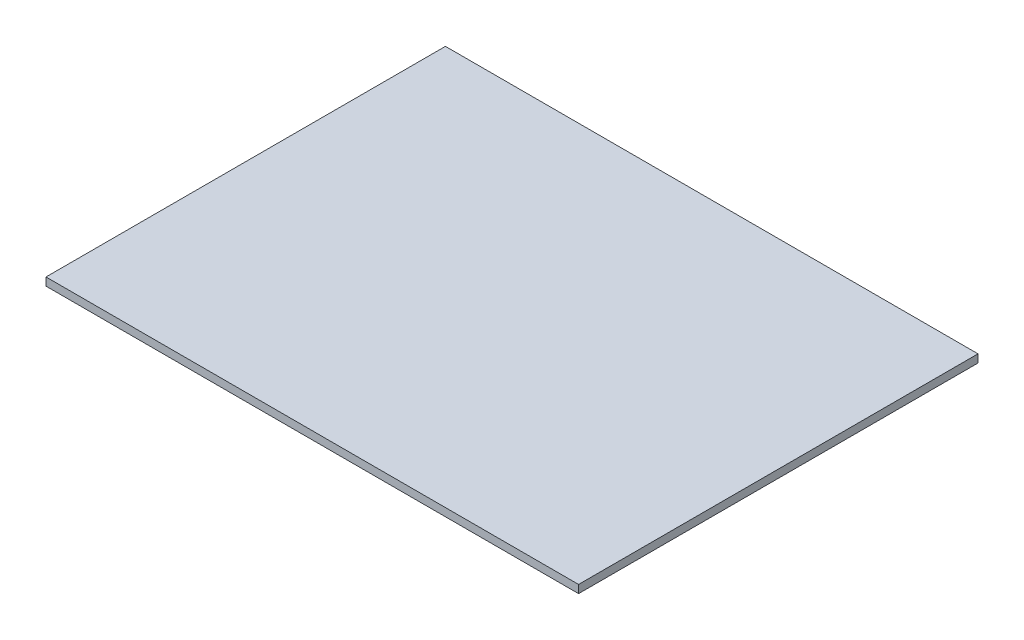
SolidWorks part; units mm, degrees
ref_plane "Front Plane" through (0, 0, 0) normal (0, 0, 1) x (1, 0, 0)
ref_plane "Top Plane" through (0, 0, 0) normal (0, 1, 0) x (1, 0, 0)
ref_plane "Right Plane" through (0, 0, 0) normal (1, 0, 0) x (0, 0, -1)
sketch "Sketch1" plane through (0, 0, 0) normal (0, 1, 0) x (1, 0, 0)
  line L1 (0, 0) -> (508, 0)
  line L2 (0, 0) -> (0, -381)
  line L3 (0, -381) -> (508, -381)
  line L4 (508, 0) -> (508, -381)
  dimension "D1" = 508
  dimension "D2" = 381
extrude "Boss-Extrude1" add sketch "Sketch1" along normal blind 7.62
